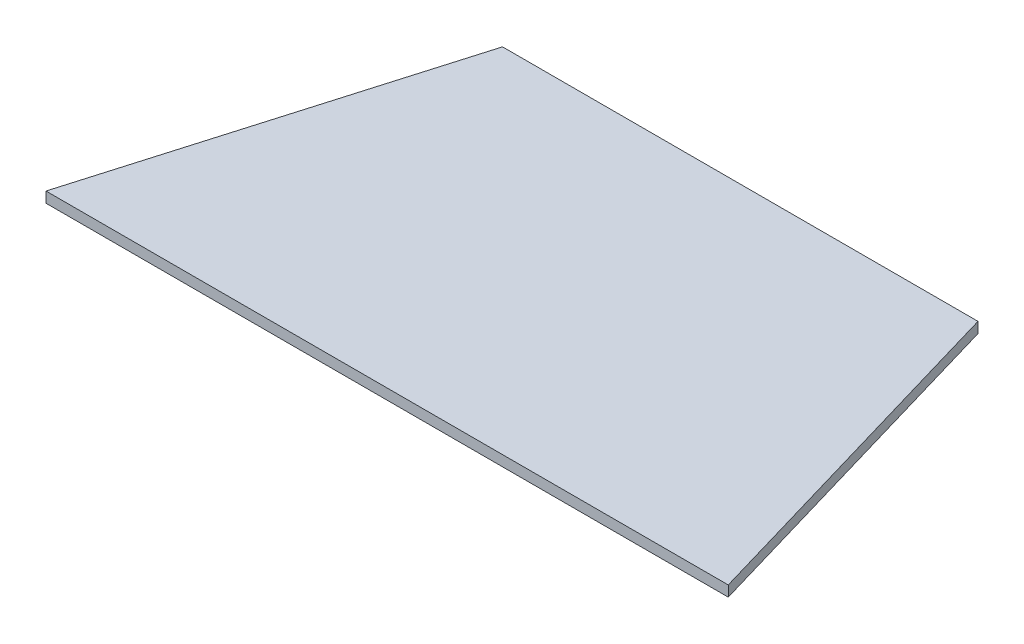
SolidWorks part; units mm, degrees
ref_plane "Front Plane" through (0, 0, 0) normal (0, 0, 1) x (1, 0, 0)
ref_plane "Top Plane" through (0, 0, 0) normal (0, 1, 0) x (1, 0, 0)
ref_plane "Right Plane" through (0, 0, 0) normal (1, 0, 0) x (0, 0, -1)
sketch "Sketch1" plane through (0, 0, 0) normal (0, 1, 0) x (1, 0, 0)
  line L0 (-13.2, 0) -> (180, 0)
  line L3 (90, 0) -> (90, 100) construction
  line L5 (-13.2, 0) -> (16.0799, 100)
  line L6 (180, 0) -> (150.7201, 100)
  line L7 (16.0799, 100) -> (150.7201, 100)
  point P2 (0, 0)
extrude "Boss-Extrude1" add sketch "Sketch1" along normal blind 3
